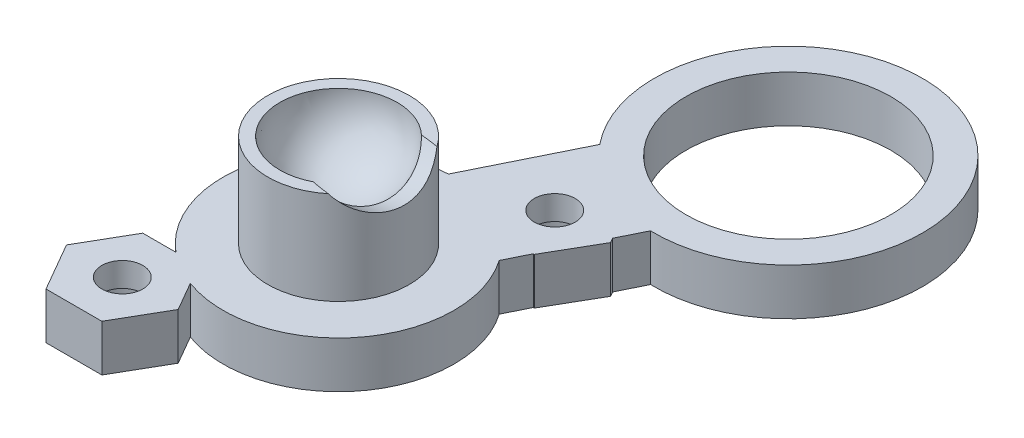
SolidWorks part; units mm, degrees
other "Compression Link 1 Moving Ball Retainer"
ref_plane "Front Plane" through (0, 0, 0) normal (0, 0, 1) x (1, 0, 0)
ref_plane "Top Plane" through (0, 0, 0) normal (0, 1, 0) x (1, 0, 0)
ref_plane "Right Plane" through (0, 0, 0) normal (1, 0, 0) x (0, 0, -1)
sketch3d "Retainer Feature 1 profile datum points"
  point P0 (-82.2724, -101, -15)
  point P1 (-72.2724, -101, -15)
  point P2 (-82.2724, -101, -5)
ref_plane "Retainer Feature 1 profile plane" through (0, -101, 0) normal (0, -1, 0) x (-1, 0, 0)
sketch "Retainer Feature 1 profile" plane through (0, -101, 0) normal (0, -1, 0) x (-1, 0, 0)
  circle A0 centre (82.2724, 15) radius 3.8
extrude "Retainer Feature 1" add sketch "Retainer Feature 1 profile" along normal blind 5.02 separate body
sketch3d "Retainer Feature 2 profile datum points"
  point P0 (-82.2724, -106, -15)
  point P1 (-72.2724, -106, -15)
  point P2 (-82.2724, -106, -5)
ref_plane "Retainer Feature 2 profile plane" through (0, -106, 0) normal (0, -1, 0) x (-1, 0, 0)
sketch "Retainer Feature 2 profile" plane through (0, -106, 0) normal (0, -1, 0) x (-1, 0, 0)
  circle A0 centre (82.2724, 15) radius 6.2
extrude "Retainer Feature 2" add sketch "Retainer Feature 2 profile" along normal blind 2.5
sketch3d "Middle Right Floating Compression Ball Retainer 1 Hexagonal Screw Pad 2 datum points"
  point P0 (-86.5224, -106, -7.6388)
  point P1 (-76.5224, -106, -7.6388)
  point P2 (-86.5224, -106, 2.3612)
ref_plane "Middle Right Floating Compression Ball Retainer 1 Hexagonal Screw Pad 2 plane" through (0, -106, 0) normal (0, -1, 0) x (-1, 0, 0)
sketch "Middle Right Floating Compression Ball Retainer 1 Hexagonal Screw Pad 2" plane through (0, -106, 0) normal (0, -1, 0) x (-1, 0, 0)
  line L0 (83.5224, 7.6388) -> (85.0224, 5.0407)
  line L1 (85.0224, 5.0407) -> (88.0224, 5.0407)
  line L2 (88.0224, 5.0407) -> (89.5224, 7.6388)
  line L3 (89.5224, 7.6388) -> (88.0224, 10.2369)
  line L4 (88.0224, 10.2369) -> (85.0224, 10.2369)
  line L5 (85.0224, 10.2369) -> (83.5224, 7.6388)
extrude "Retainer Feature 5" add sketch "Middle Right Floating Compression Ball Retainer 1 Hexagonal Screw Pad 2" along normal blind 2.5
sketch3d "Middle Right Floating Compression Ball Retainer 1 Hexagonal Screw Pad 5 datum points"
  point P0 (-78.0224, -106, -22.3612)
  point P1 (-68.0224, -106, -22.3612)
  point P2 (-78.0224, -106, -12.3612)
ref_plane "Middle Right Floating Compression Ball Retainer 1 Hexagonal Screw Pad 5 plane" through (0, -106, 0) normal (0, -1, 0) x (-1, 0, 0)
sketch "Middle Right Floating Compression Ball Retainer 1 Hexagonal Screw Pad 5" plane through (0, -106, 0) normal (0, -1, 0) x (-1, 0, 0)
  line L0 (75.0224, 22.3612) -> (76.5224, 19.7631)
  line L1 (76.5224, 19.7631) -> (79.5224, 19.7631)
  line L2 (79.5224, 19.7631) -> (81.0224, 22.3612)
  line L3 (81.0224, 22.3612) -> (79.5224, 24.9593)
  line L4 (79.5224, 24.9593) -> (76.5224, 24.9593)
  line L5 (76.5224, 24.9593) -> (75.0224, 22.3612)
extrude "Retainer Feature 8" add sketch "Middle Right Floating Compression Ball Retainer 1 Hexagonal Screw Pad 5" along normal blind 2.5
sketch3d "Retainer Feature 9 axis line"
  line L0 (-82.2724, -101, -25) -> (-82.2724, -101, -5) construction
ref_axis "Retainer Feature 9 axis" through (-82.2724, -101, -25) along (0, 0, 1)
sketch3d "Retainer Feature 9 profile datum points"
  point P0 (-82.2724, -101, -15)
  point P1 (-72.2724, -101, -15)
  point P2 (-82.2724, -101, -5)
ref_plane "Retainer Feature 9 profile plane" through (0, -101, 0) normal (0, -1, 0) x (-1, 0, 0)
sketch "Retainer Feature 9 profile" plane through (0, -101, 0) normal (0, -1, 0) x (-1, 0, 0)
  line L0 (82.2724, 11.85) -> (82.2724, 18.15)
  arc A0 (82.2724, 18.15) -> (82.2724, 11.85) centre (82.2724, 15) ccw
revolve "Retainer Feature 9" cut sketch "Retainer Feature 9 profile" angle 360 about axis through (-82.2724, -101, -25) along (0, 0, 1)
sketch3d "Middle Right Floating Compression Ball Retainer 1 Plate Sketch 49 datum points"
  point P0 (-82.2724, -106, -15)
  point P1 (-77.8481, -106, -23.968)
  point P2 (-73.3044, -106, -10.5757)
ref_plane "Middle Right Floating Compression Ball Retainer 1 Plate Sketch 49 plane" through (0, -106, 0) normal (0, -1, 0) x (-1, 0, 0)
sketch "Middle Right Floating Compression Ball Retainer 1 Plate Sketch 49" plane through (0, -106, 0) normal (0, -1, 0) x (-1, 0, 0)
  line L0 (84.9628, 16.3273) -> (76.9821, 32.5042)
  line L1 (76.9821, 32.5042) -> (71.6012, 29.8496)
  line L2 (71.6012, 29.8496) -> (79.582, 13.6727)
  line L3 (79.582, 13.6727) -> (84.9628, 16.3273)
extrude "Retainer Feature 12" add sketch "Middle Right Floating Compression Ball Retainer 1 Plate Sketch 49" along normal blind 2.5
sketch3d "Retainer Feature 13 profile datum points"
  point P0 (-74.2917, -106, -31.1769)
  point P1 (-64.2917, -106, -31.1769)
  point P2 (-74.2917, -106, -21.1769)
ref_plane "Retainer Feature 13 profile plane" through (0, -106, 0) normal (0, -1, 0) x (-1, 0, 0)
sketch "Retainer Feature 13 profile" plane through (0, -106, 0) normal (0, -1, 0) x (-1, 0, 0)
  circle A0 centre (74.2917, 31.1769) radius 7.2
extrude "Retainer Feature 13" add sketch "Retainer Feature 13 profile" along normal blind 2.5
sketch3d "Retainer Feature 14 profile datum points"
  point P0 (-74.2917, -105.9, -31.1769)
  point P1 (-64.2917, -105.9, -31.1769)
  point P2 (-74.2917, -105.9, -21.1769)
ref_plane "Retainer Feature 14 profile plane" through (0, -105.9, 0) normal (0, -1, 0) x (-1, 0, 0)
sketch "Retainer Feature 14 profile" plane through (0, -105.9, 0) normal (0, -1, 0) x (-1, 0, 0)
  circle A0 centre (74.2917, 31.1769) radius 5.5
extrude "Retainer Feature 14" cut sketch "Retainer Feature 14 profile" along normal blind 2.7
sketch3d "Retainer Feature 15 profile datum points"
  point P0 (-86.5224, -105, -7.6388)
  point P1 (-76.5224, -105, -7.6388)
  point P2 (-86.5224, -105, 2.3612)
ref_plane "Retainer Feature 15 profile plane" through (0, -105, 0) normal (0, -1, 0) x (-1, 0, 0)
sketch "Retainer Feature 15 profile" plane through (0, -105, 0) normal (0, -1, 0) x (-1, 0, 0)
  circle A0 centre (86.5224, 7.6388) radius 1.1
extrude "Retainer Feature 15" cut sketch "Retainer Feature 15 profile" along normal blind 3.75
sketch3d "Retainer Feature 16 profile datum points"
  point P0 (-86.5224, -107.3, -7.6388)
  point P1 (-76.5224, -107.3, -7.6388)
  point P2 (-86.5224, -107.3, 2.3612)
ref_plane "Retainer Feature 16 profile plane" through (0, -107.3, 0) normal (0, -1, 0) x (-1, 0, 0)
sketch "Retainer Feature 16 profile" plane through (0, -107.3, 0) normal (0, -1, 0) x (-1, 0, 0)
  circle A0 centre (86.5224, 7.6388) radius 2.1
extrude "Retainer Feature 16" cut sketch "Retainer Feature 16 profile" along normal blind 1.45
sketch3d "Retainer Feature 17 profile datum points"
  point P0 (-78.0224, -105, -22.3612)
  point P1 (-68.0224, -105, -22.3612)
  point P2 (-78.0224, -105, -12.3612)
ref_plane "Retainer Feature 17 profile plane" through (0, -105, 0) normal (0, -1, 0) x (-1, 0, 0)
sketch "Retainer Feature 17 profile" plane through (0, -105, 0) normal (0, -1, 0) x (-1, 0, 0)
  circle A0 centre (78.0224, 22.3612) radius 1.1
extrude "Retainer Feature 17" cut sketch "Retainer Feature 17 profile" along normal blind 3.75
sketch3d "Retainer Feature 18 profile datum points"
  point P0 (-78.0224, -107.3, -22.3612)
  point P1 (-68.0224, -107.3, -22.3612)
  point P2 (-78.0224, -107.3, -12.3612)
ref_plane "Retainer Feature 18 profile plane" through (0, -107.3, 0) normal (0, -1, 0) x (-1, 0, 0)
sketch "Retainer Feature 18 profile" plane through (0, -107.3, 0) normal (0, -1, 0) x (-1, 0, 0)
  circle A0 centre (78.0224, 22.3612) radius 2.1
extrude "Retainer Feature 18" cut sketch "Retainer Feature 18 profile" along normal blind 1.45
sketch3d "Articulation Throat axis line"
  line L0 (-90.6158, -106.3831, -16.1872) -> (-73.929, -95.6169, -13.8128) construction
ref_axis "Articulation Throat axis" through (-90.6158, -106.3831, -16.1872) along (0.8343, 0.5383, 0.1187)
sketch3d "Articulation Throat Sketch datum points"
  point P0 (-82.2724, -101, -15)
  point P1 (-82.2724, -98.8462, -24.7653)
  point P2 (-73.929, -95.6169, -13.8128)
ref_plane "Articulation Throat Sketch plane" through (21.8481, -32.2924, -7.1221) normal (0.5512, -0.8148, -0.1797) x (-0.8343, -0.5383, -0.1187)
sketch "Articulation Throat Sketch" plane through (21.8481, -32.2924, -7.1221) normal (0.5512, -0.8148, -0.1797) x (-0.8343, -0.5383, -0.1187)
  line L0 (124.7935, -7.105) -> (124.7935, -4.805)
  line L1 (124.7935, -4.805) -> (101.7935, 1.915)
  line L2 (101.7935, 1.915) -> (101.7935, -7.105)
  line L3 (101.7935, -7.105) -> (124.7935, -7.105)
revolve "Articulation Throat" cut sketch "Articulation Throat Sketch" angle 360 about axis through (-90.6158, -106.3831, -16.1872) along (0.8343, 0.5383, 0.1187)
